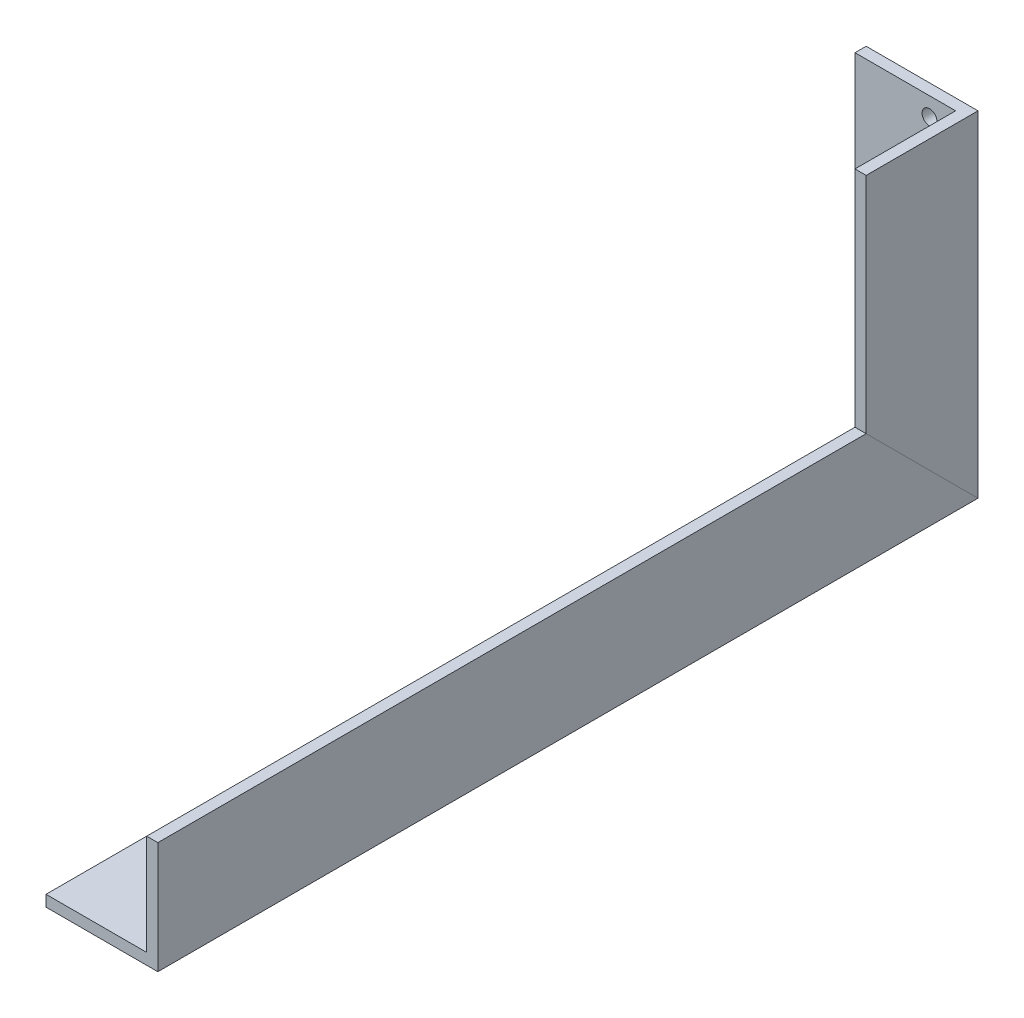
SolidWorks part; units mm, degrees
ref_plane "Front Plane" through (0, 0, 0) normal (0, 0, 1) x (1, 0, 0)
ref_plane "Top Plane" through (0, 0, 0) normal (0, 1, 0) x (1, 0, 0)
ref_plane "Right Plane" through (0, 0, 0) normal (1, 0, 0) x (0, 0, -1)
sketch "Sketch2" plane through (0, 0, 0) normal (0, 0, 1) x (1, 0, 0)
  line L0 (0, 0) -> (30, 0)
  line L1 (30, 0) -> (30, 30)
  line L5 (0, 3) -> (0, 0)
  line L6 (30, 30) -> (27, 30)
  line L7 (27, 30) -> (27, 3)
  line L8 (27, 3) -> (0, 3)
  dimension "D1" = 30
  dimension "D2" = 30
  dimension "D3" = 3
  dimension "D5" = 3
sketch "Sketch4" plane through (0, 0, 0) normal (1, 0, 0) x (0, 0, -1)
  line L0 (0, 0) -> (220, 0)
  line L1 (220, 0) -> (220, 90)
  dimension "D1" = 220
  dimension "D2" = 90
sweep "Sweep1" add profiles "Sketch2" path "Sketch4"
sketch "Sketch7" plane through (0, 0, -220) normal (0, 0, -1) x (-1, 0, 0)
  circle A0 centre (-20, 85) radius 2 construction
  circle A1 centre (-20, 85) radius 2
extrude "Cut-Extrude1" cut sketch "Sketch7" against normal blind 10 contours A1
